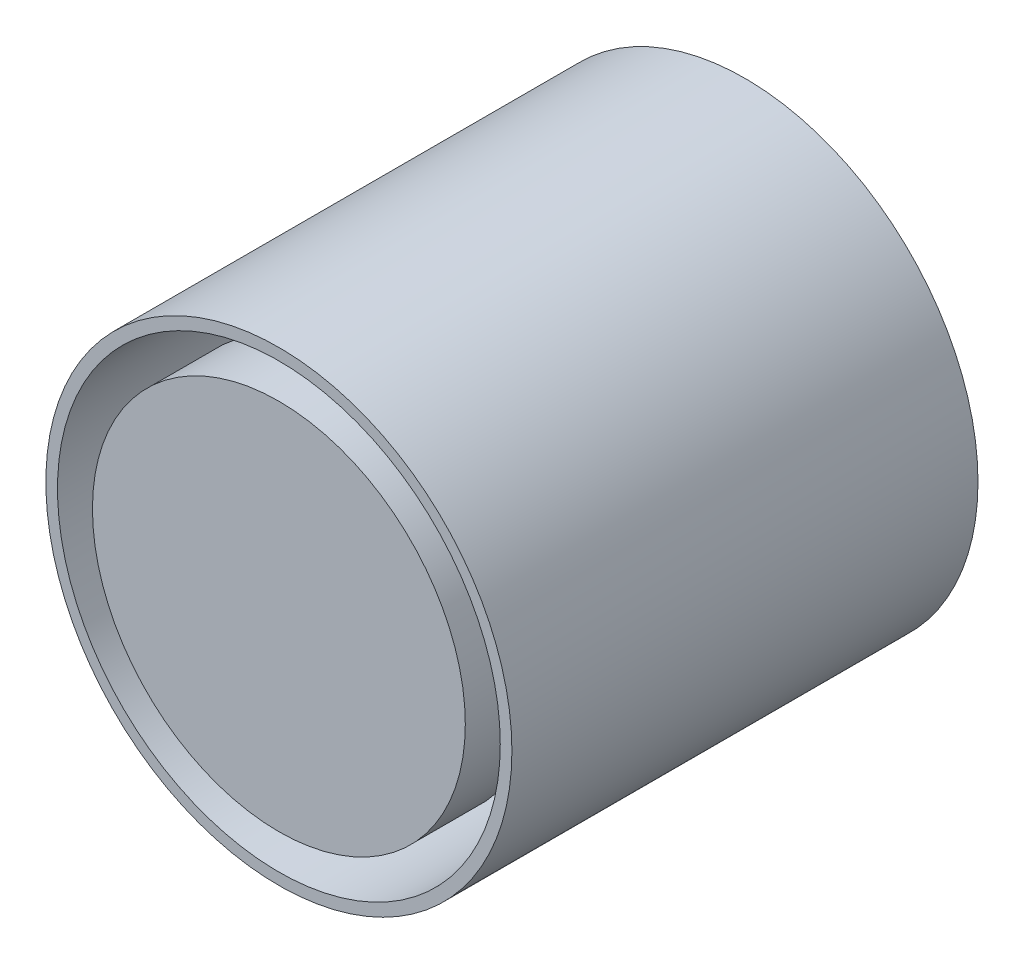
SolidWorks part; units mm, degrees
other "标注1"
sketch "草图5" plane through (100, 100, 200) normal (0.461, 0.308, 0.8323) x (-0.7479, 0.6396, 0.1776)
ref_plane "前视基准面" through (0, 0, 0) normal (0, 0, 1) x (1, 0, 0)
ref_plane "上视基准面" through (0, 0, 0) normal (0, 1, 0) x (1, 0, 0)
ref_plane "右视基准面" through (0, 0, 0) normal (1, 0, 0) x (0, 0, -1)
other "Configuration Table"
sketch "草图2" plane through (0, 0, 0) normal (0, 0, 1) x (1, 0, 0)
  circle A0 centre (0, 0) radius 100
extrude "凸台-拉伸2" add sketch "草图2" along normal blind 200
sketch "草图3" plane through (0, 0, 200) normal (0, 0, 1) x (1, 0, 0)
  circle A0 centre (0, 0) radius 95
extrude "切除-拉伸1" cut sketch "草图3" against normal blind 400
sketch "草图4" plane through (0, 0, 0) normal (0, 0, -1) x (-1, 0, 0)
  circle A0 centre (0, 0) radius 80
extrude "凸台-拉伸3" add sketch "草图4" against normal blind 30 separate body
move or copy body "实体-移动/复制3" bodies to move or copy 110 copy no translate (0, 0, 170) parameters "D1"=0, "D2"=0, "D3"=170
